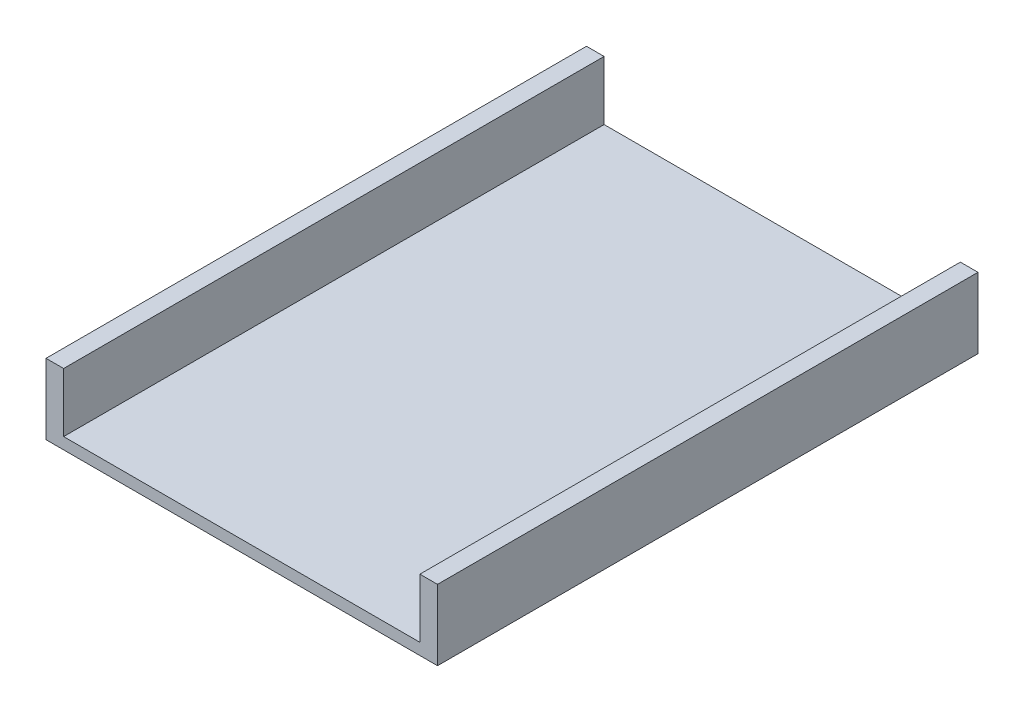
SolidWorks part; units mm, degrees
ref_plane "Front Plane" through (0, 0, 0) normal (0, 0, 1) x (1, 0, 0)
ref_plane "Top Plane" through (0, 0, 0) normal (0, 1, 0) x (1, 0, 0)
ref_plane "Right Plane" through (0, 0, 0) normal (1, 0, 0) x (0, 0, -1)
sketch "Sketch1" plane through (0, 0, 0) normal (0, 0, 1) x (1, 0, 0)
  line L0 (-36.0467, 56.7507) -> (-16.9967, 56.7507)
  line L1 (-16.9967, 56.7507) -> (-16.9967, -7.0033)
  line L2 (-16.9967, -7.0033) -> (368.0673, -7.0033)
  line L6 (65.3632, -19.4493) -> (-36.0467, -19.4493)
  line L7 (-36.0467, -19.4493) -> (-36.0467, 56.7507)
  line L10 (368.0673, -7.0033) -> (368.0673, 56.7507)
  line L11 (65.3632, -19.4493) -> (387.1173, -19.4493)
  line L12 (387.1173, -19.4493) -> (387.1173, 56.7507)
  line L13 (387.1173, 56.7507) -> (368.0673, 56.7507)
  dimension "D1" = 19.05
  dimension "D2" = 12.446
  dimension "D3" = 385.064
  dimension "D4" = 19.05
  dimension "D5" = 76.2
  dimension "D6" = 76.2
extrude "Boss-Extrude1" add sketch "Sketch1" along normal blind 584.2
